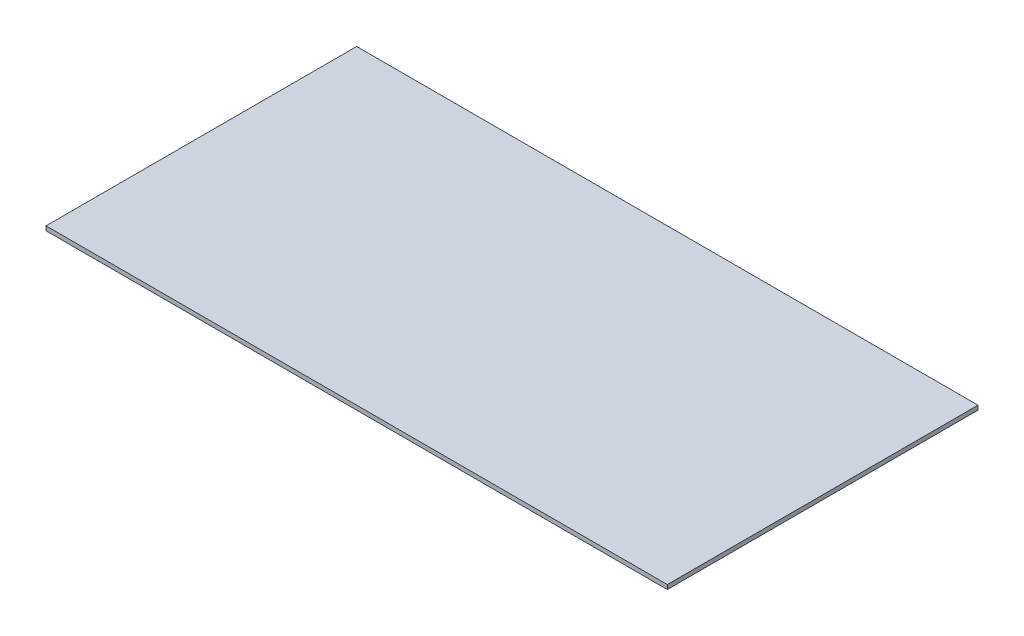
SolidWorks part; units mm, degrees
material "Pine"
ref_plane "Front Plane" through (0, 0, 0) normal (0, 0, 1) x (1, 0, 0)
ref_plane "Top Plane" through (0, 0, 0) normal (0, 1, 0) x (1, 0, 0)
ref_plane "Right Plane" through (0, 0, 0) normal (1, 0, 0) x (0, 0, -1)
sketch "Sketch1" plane through (0, 0, 0) normal (0, 1, 0) x (1, 0, 0)
  line L1 (914.4, -457.2) -> (-914.4, -457.2)
  line L2 (914.4, -457.2) -> (914.4, 457.2)
  line L3 (914.4, 457.2) -> (-914.4, 457.2)
  line L4 (-914.4, -457.2) -> (-914.4, 457.2)
  line L5 (914.4, -457.2) -> (-914.4, 457.2) construction
  line L6 (914.4, 457.2) -> (-914.4, -457.2) construction
  point P0 (0, 0)
  dimension "D1" = 1828.8
  dimension "D2" = 914.4
extrude "Boss-Extrude1" add sketch "Sketch1" along normal blind 12.7
